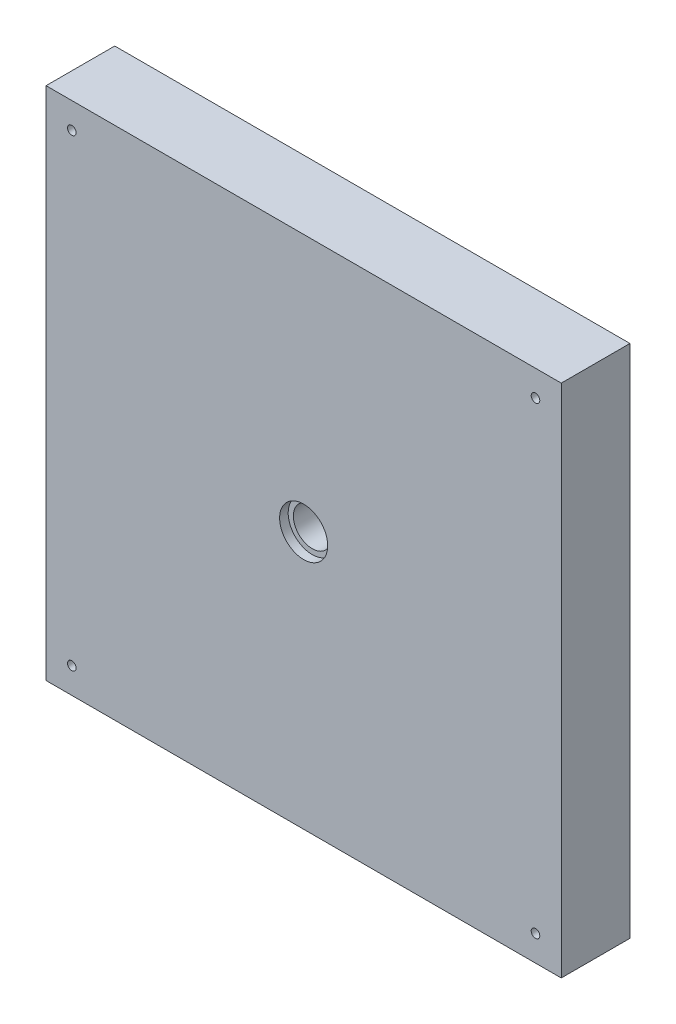
SolidWorks part; units mm, degrees
ref_plane "正面" through (0, 0, 0) normal (0, 0, 1) x (1, 0, 0)
ref_plane "平面" through (0, 0, 0) normal (0, 1, 0) x (1, 0, 0)
ref_plane "右側面" through (0, 0, 0) normal (1, 0, 0) x (0, 0, -1)
sketch "ｽｹｯﾁ1" plane through (0, 0, 0) normal (0, 0, 1) x (1, 0, 0)
  line L1 (0, 0) -> (300, 0)
  line L2 (0, 0) -> (0, -300)
  line L3 (0, -300) -> (300, -300)
  line L4 (300, 0) -> (300, -300)
  dimension "D1" = 300
  dimension "D2" = 300
extrude "ﾎﾞｽ - 押し出し1" add sketch "ｽｹｯﾁ1" along normal blind 40
sketch "ｽｹｯﾁ2" plane through (0, 0, 40) normal (0, 0, 1) x (1, 0, 0)
  line L0 (0, 0) -> (150, 0) construction
  line L1 (300, 0) -> (0, 0) construction
  line L2 (150, 0) -> (150, -300) construction
  line L3 (0, -300) -> (300, -300) construction
  line L4 (150, -300) -> (0, -300) construction
  line L5 (0, -300) -> (0, -150) construction
  line L6 (0, 0) -> (0, -300) construction
  line L7 (0, -150) -> (150, -150) construction
  circle A0 centre (150, -150) radius 11
  dimension "D1" = 22
extrude "ｶｯﾄ - 押し出し1" cut sketch "ｽｹｯﾁ2" against normal through all
sketch "ｽｹｯﾁ3" plane through (0, 0, 40) normal (0, 0, 1) x (1, 0, 0)
  circle A0 centre (150, -150) radius 14
  dimension "D1" = 28
sketch "ｽｹｯﾁ4" plane through (0, 0, 0) normal (0, 0, -1) x (-1, 0, 0)
  line L0 (0, 0) -> (-150, 0) construction
  line L1 (-300, 0) -> (0, 0) construction
  line L2 (-150, 0) -> (-150, -150) construction
  line L3 (-150, -150) -> (0, -150) construction
  line L4 (0, 0) -> (0, -300) construction
  line L5 (-150, -150) -> (-300, -150) construction
  line L6 (-300, -300) -> (-300, 0) construction
  line L7 (-300, -150) -> (-150, -150) construction
  line L8 (-150, -150) -> (-150, -300) construction
  line L9 (0, -300) -> (-300, -300) construction
  circle A0 centre (-150, -150) radius 110
  circle A1 centre (-40, -150) radius 2.75
  circle A2 centre (-150, -40) radius 2.75
  circle A3 centre (-260, -150) radius 2.75
  circle A4 centre (-150, -260) radius 2.75
  dimension "D1" = 220
  dimension "D2" = 5.5
  dimension "D3" = 5.5
  dimension "D4" = 5.5
  dimension "D5" = 5.5
hole_wizard "M6x1.0 ねじ穴1" positions "ｽｹｯﾁ6" profile "ｽｹｯﾁ7" tap size "M6x1.0" standard "JIS"
sketch "ｽｹｯﾁ6" plane through (0, 0, 0) normal (0, 0, -1) x (-1, 0, 0)
  point P0 (-260, -150)
sketch "ｽｹｯﾁ7" plane through (260, -150, 0) normal (1, 0, 0) x (0, 1, 0)
  line L0 (0, 0) -> (0, 18.5022)
  line L1 (0, 18.5022) -> (2.5, 17)
  line L2 (2.5, 17) -> (2.5, 0)
  line L5 (2.5, 0) -> (0, 0)
  line L10 (0, 18.5022) -> (-2.5, 17) construction
  line L11 (0, -6.35) -> (0, 107.95) construction
  dimension "ねじ下穴ﾄﾞﾘﾙ直径" = 5
  dimension "ねじ下穴ﾄﾞﾘﾙの深さ" = 17
  dimension "ﾄﾞﾘﾙ角度" = 118
hole_wizard "M6x1.0 ねじ穴2" positions "ｽｹｯﾁ13" profile "ｽｹｯﾁ14" tap size "M6x1.0" standard "JIS"
sketch "ｽｹｯﾁ13" plane through (0, 0, 0) normal (0, 0, -1) x (-1, 0, 0)
  point P0 (-150, -40)
sketch "ｽｹｯﾁ14" plane through (150, -40, 0) normal (1, 0, 0) x (0, 1, 0)
  line L0 (0, 0) -> (0, 18.5022)
  line L1 (0, 18.5022) -> (2.5, 17)
  line L2 (2.5, 17) -> (2.5, 0)
  line L5 (2.5, 0) -> (0, 0)
  line L10 (0, 18.5022) -> (-2.5, 17) construction
  line L11 (0, -6.35) -> (0, 107.95) construction
  dimension "ねじ下穴ﾄﾞﾘﾙ直径" = 5
  dimension "ねじ下穴ﾄﾞﾘﾙの深さ" = 17
  dimension "ﾄﾞﾘﾙ角度" = 118
cosmetic thread "穴のねじ山4" parameters "D1"=12, "D2"=6
hole_wizard "M6x1.0 ねじ穴3" positions "3Dｽｹｯﾁ2" profile "ｽｹｯﾁ15" tap size "M6x1.0" standard "JIS"
sketch3d "3Dｽｹｯﾁ2"
  point P0 (40, -150, 0)
sketch "ｽｹｯﾁ15" plane through (40, -150, 0) normal (1, 0, 0) x (0, 1, 0)
  line L0 (0, 0) -> (0, 18.5022)
  line L1 (0, 18.5022) -> (2.5, 17)
  line L2 (2.5, 17) -> (2.5, 0)
  line L5 (2.5, 0) -> (0, 0)
  line L10 (0, 18.5022) -> (-2.5, 17) construction
  line L11 (0, -6.35) -> (0, 107.95) construction
  dimension "ねじ下穴ﾄﾞﾘﾙ直径" = 5
  dimension "ねじ下穴ﾄﾞﾘﾙの深さ" = 17
  dimension "ﾄﾞﾘﾙ角度" = 118
cosmetic thread "穴のねじ山5" parameters "D1"=12, "D2"=6
hole_wizard "M6x1.0 ねじ穴4" positions "3Dｽｹｯﾁ3" profile "ｽｹｯﾁ16" tap size "M6x1.0" standard "JIS"
sketch3d "3Dｽｹｯﾁ3"
  point P0 (150, -260, 0)
sketch "ｽｹｯﾁ16" plane through (150, -260, 0) normal (1, 0, 0) x (0, 1, 0)
  line L0 (0, 0) -> (0, 18.5022)
  line L1 (0, 18.5022) -> (2.5, 17)
  line L2 (2.5, 17) -> (2.5, 0)
  line L5 (2.5, 0) -> (0, 0)
  line L10 (0, 18.5022) -> (-2.5, 17) construction
  line L11 (0, -6.35) -> (0, 107.95) construction
  dimension "ねじ下穴ﾄﾞﾘﾙ直径" = 5
  dimension "ねじ下穴ﾄﾞﾘﾙの深さ" = 17
  dimension "ﾄﾞﾘﾙ角度" = 118
cosmetic thread "穴のねじ山6" parameters "D1"=12, "D2"=6
extrude "ｶｯﾄ - 押し出し2" cut sketch "ｽｹｯﾁ3" against normal blind 5 contours A0
chamfer "面取り1" distance 1 angle 45 1 edges at (257.5, -150, 0)
chamfer "面取り2" distance 1 angle 45 1 edges at (147.5, -40, 0)
chamfer "面取り3" distance 1 angle 45 1 edges at (147.5, -260, 0)
chamfer "面取り4" distance 1 angle 45 1 edges at (37.5, -150, 0)
sketch "ｽｹｯﾁ17" plane through (0, 0, 0) normal (0, 0, -1) x (-1, 0, 0)
  line L0 (-300, -300) -> (-300, -285) construction
  line L1 (-300, -300) -> (-300, 0) construction
  line L2 (-300, -285) -> (-285, -285) construction
  line L3 (-285, -285) -> (0, -285) construction
  line L4 (0, 0) -> (0, -300) construction
  line L5 (0, -285) -> (-15, -285) construction
  line L6 (-15, -285) -> (-15, 0) construction
  line L7 (0, 0) -> (-150, 0) construction
  line L8 (-15, 0) -> (-15, -15) construction
  line L9 (-15, -15) -> (-300, -15) construction
  line L10 (-300, -15) -> (-285, -15) construction
  dimension "D1" = 15
  dimension "D2" = 15
  dimension "D3" = 15
  dimension "D4" = 15
  dimension "D5" = 15
hole_wizard "M6x1.0 ねじ穴5" positions "3Dｽｹｯﾁ4" profile "ｽｹｯﾁ18" tap size "M6x1.0" standard "JIS" end condition through all
sketch3d "3Dｽｹｯﾁ4"
  point P0 (285, -15, 0)
  point P3 (15, -15, 0)
  point P6 (15, -285, 0)
  point P9 (285, -285, 0)
sketch "ｽｹｯﾁ18" plane through (285, -15, 0) normal (1, 0, 0) x (0, 1, 0)
  line L0 (0, 0) -> (0, 40)
  line L1 (0, 40) -> (2.5, 40)
  line L2 (2.5, 40) -> (2.5, 0)
  line L5 (2.5, 0) -> (0, 0)
  line L11 (0, -6.35) -> (0, 107.95) construction
  dimension "次ｻｰﾌｪｽまでのねじ下穴ﾄﾞﾘﾙ直径" = 5
  dimension "次ｻｰﾌｪｽまでのねじ下穴ﾄﾞﾘﾙの深さ" = 40
cosmetic thread "穴のねじ山7" parameters "D2"=6
cosmetic thread "穴のねじ山8" parameters "D2"=6
cosmetic thread "穴のねじ山9" parameters "D2"=6
cosmetic thread "穴のねじ山10" parameters "D2"=6
